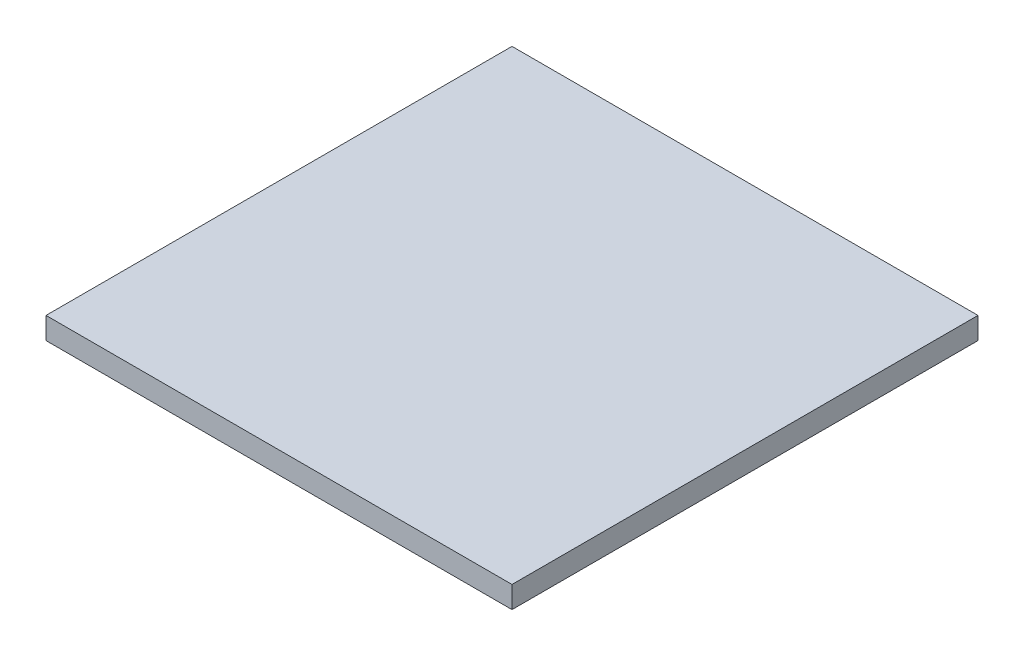
SolidWorks part; units mm, degrees
ref_plane "Front Plane" through (0, 0, 0) normal (0, 0, 1) x (1, 0, 0)
ref_plane "Top Plane" through (0, 0, 0) normal (0, 1, 0) x (1, 0, 0)
ref_plane "Right Plane" through (0, 0, 0) normal (1, 0, 0) x (0, 0, -1)
sketch "Sketch1" plane through (0, 0, 0) normal (0, 1, 0) x (1, 0, 0)
  line L1 (-149.225, -149.225) -> (149.225, -149.225)
  line L2 (-149.225, -149.225) -> (-149.225, 149.225)
  line L3 (-149.225, 149.225) -> (149.225, 149.225)
  line L4 (149.225, -149.225) -> (149.225, 149.225)
  line L5 (-149.225, -149.225) -> (149.225, 149.225) construction
  line L6 (-149.225, 149.225) -> (149.225, -149.225) construction
  point P0 (0, 0)
  dimension "D1" = 298.45
extrude "Boss-Extrude1" add sketch "Sketch1" along normal blind 13.97
